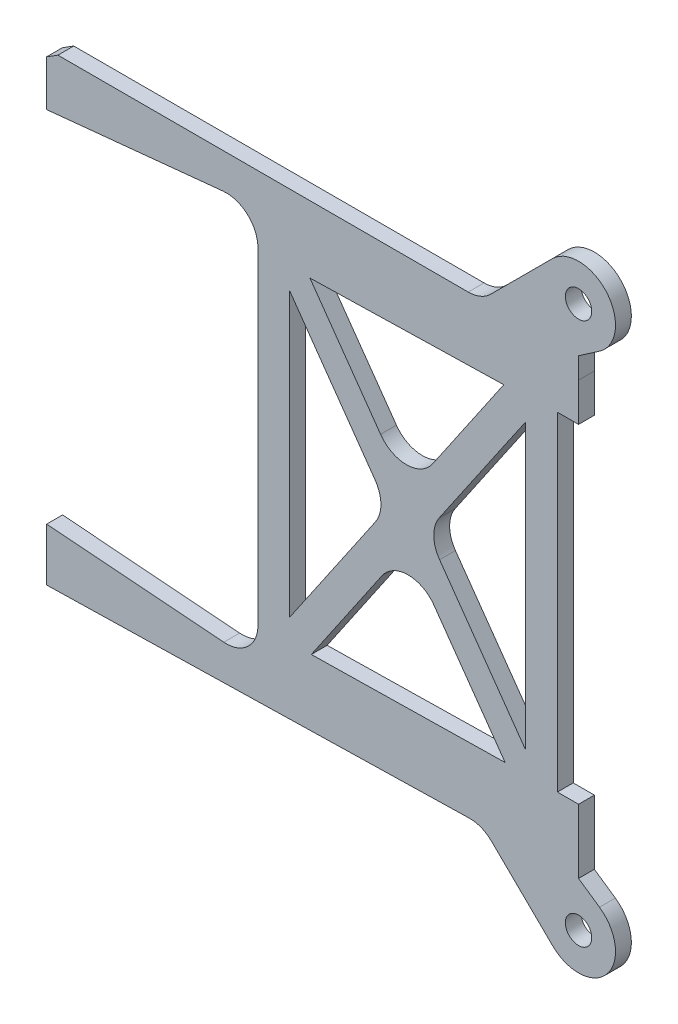
SolidWorks part; units mm, degrees
ref_plane "前视基准面" through (0, 0, 0) normal (0, 0, 1) x (1, 0, 0)
ref_plane "上视基准面" through (0, 0, 0) normal (0, 1, 0) x (1, 0, 0)
ref_plane "右视基准面" through (0, 0, 0) normal (1, 0, 0) x (0, 0, -1)
sketch "Model" plane through (0, 0, 0) normal (0, 0, 1) x (1, 0, 0)
  line L0 (580.9956, 495.7703) -> (600.9025, 495.7703)
  line L1 (580.9956, 489.4553) -> (580.9956, 458.4872)
  line L2 (580.9956, 452.245) -> (600.9426, 452.6903)
  line L3 (580.9956, 495.7703) -> (562.0624, 495.7703)
  line L4 (560.9956, 495.1009) -> (560.9956, 490.7703)
  line L5 (560.9956, 490.7703) -> (577.6971, 492.4404)
  line L6 (580.9956, 452.245) -> (561.0006, 451.7987)
  line L7 (561.0006, 451.7987) -> (561.0006, 456.7987)
  line L8 (561.0006, 456.7987) -> (577.7632, 455.4962)
  line L9 (585.9165, 489.4264) -> (604.2674, 489.8574)
  line L10 (586.0474, 458.6328) -> (604.397, 458.9518)
  line L11 (583.9951, 460.6498) -> (583.9955, 487.4275)
  line L12 (606.3451, 460.9338) -> (606.3465, 487.8582)
  line L13 (583.9955, 487.4275) -> (592.0898, 475.9575)
  line L14 (585.9165, 489.4264) -> (592.6055, 479.961)
  line L15 (583.9951, 460.6498) -> (592.1157, 472.5354)
  line L16 (592.7373, 468.4315) -> (586.0474, 458.6328)
  line L17 (597.6643, 468.4721) -> (604.397, 458.9518)
  line L18 (597.5325, 480) -> (604.2674, 489.8574)
  line L19 (606.3465, 487.8582) -> (598.1641, 475.8988)
  line L20 (598.1901, 472.4735) -> (606.3451, 460.9338)
  line L21 (611.3449, 490.1399) -> (609.3449, 490.1399)
  line L22 (611.3449, 459.0035) -> (609.3449, 459.0035)
  line L23 (609.3449, 490.1399) -> (609.3449, 459.0035)
  line L24 (611.3449, 454.9225) -> (611.3449, 452.9225)
  line L25 (611.3449, 493.7703) -> (611.3449, 495.7703)
  line L26 (607.6496, 447.3944) -> (603.1308, 451.8257)
  line L27 (608.87, 502.4952) -> (603.0238, 496.649)
  line L28 (611.3449, 495.7703) -> (613.3304, 497.1379)
  line L29 (607.6496, 447.3944) -> (608.87, 446.1977)
  line L30 (611.3449, 452.9225) -> (613.3304, 451.5549)
  line L31 (611.3449, 459.0035) -> (611.3449, 454.9225)
  line L32 (611.3449, 493.7703) -> (611.3449, 490.1399)
  line L33 (560.9956, 495.1009) -> (562.0624, 495.7703)
  arc A0 (600.9025, 495.7703) -> (603.0238, 496.649) centre (600.9025, 498.7703) ccw
  arc A1 (577.7632, 455.4962) -> (580.9956, 458.4872) centre (577.9956, 458.4872) ccw
  arc A2 (580.9956, 489.4553) -> (577.6971, 492.4404) centre (577.9956, 489.4553) ccw
  arc A4 (603.1308, 451.8257) -> (600.9426, 452.6903) centre (601.0547, 449.7729) ccw
  arc A6 (592.1157, 472.5354) -> (592.0898, 475.9575) centre (589.6387, 474.2278) ccw
  arc A7 (597.6643, 468.4721) -> (592.7373, 468.4315) centre (595.2149, 466.7399) ccw
  arc A8 (592.6055, 479.961) -> (597.5325, 480) centre (595.0555, 481.6924) ccw
  arc A9 (598.1641, 475.8988) -> (598.1901, 472.4735) centre (600.6401, 474.2048) ccw
  circle A14 centre (611.3449, 500.0203) radius 1.25
  circle A15 centre (611.3449, 448.6725) radius 1.25
  arc A16 (608.87, 446.1977) -> (613.3304, 451.5549) centre (611.3449, 448.6725) ccw
  arc A17 (613.3304, 497.1379) -> (608.87, 502.4952) centre (611.3449, 500.0203) ccw
extrude "凸台-拉伸1" add sketch "Model" along normal blind 1.5
